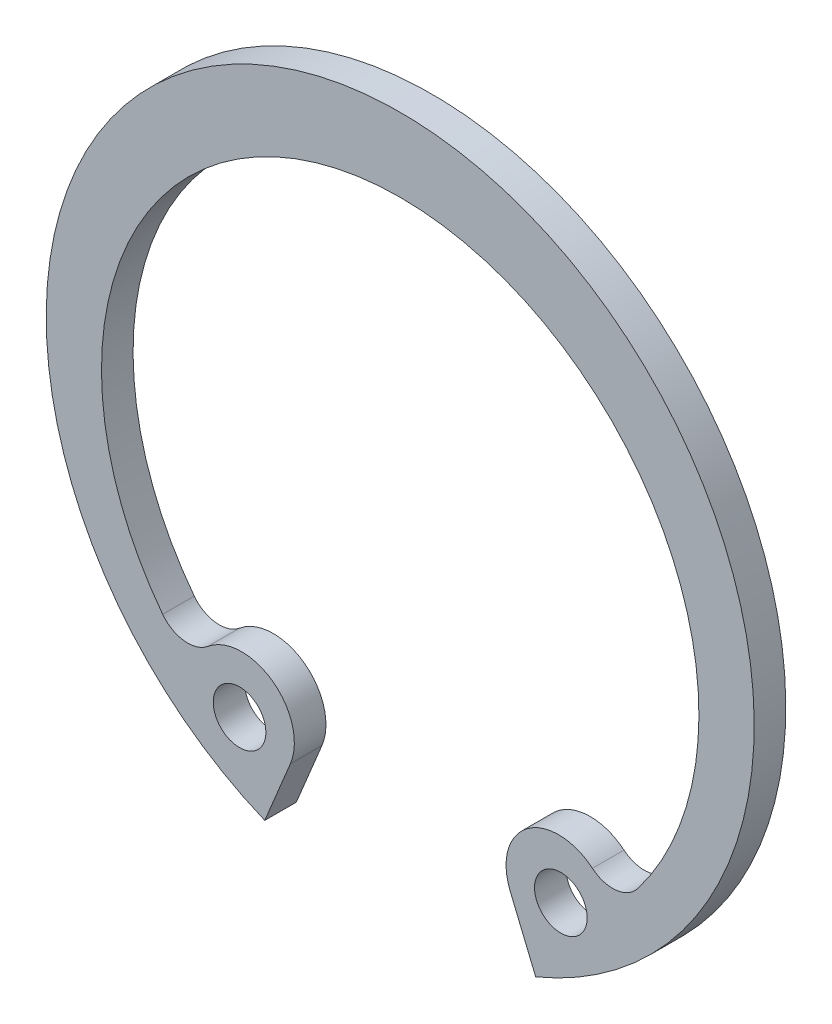
SolidWorks part; units mm, degrees
ref_plane "前视" through (0, 0, 0) normal (0, 0, 1) x (1, 0, 0)
ref_plane "上视" through (0, 0, 0) normal (0, 1, 0) x (1, 0, 0)
ref_plane "右视" through (0, 0, 0) normal (1, 0, 0) x (0, 0, -1)
sketch "尺寸草图" plane through (0, 0, 0) normal (0, 0, 1) x (1, 0, 0)
  line L0 (-13.45, 0) -> (13.45, 0) construction
  line L1 (0, 0) -> (-11.648, -6.725) construction
  circle A0 centre (0, 0) radius 13.45
  point P5 (-9.25, 0)
  point P6 (2, 0)
  point P7 (2, 0)
  point P8 (3.2, 0)
  point P10 (-2.5, 0)
  point P11 (-0.7, 0)
  point P12 (-4.5, 0)
  point P13 (-10.45, 0)
  point P14 (27.3231, 15.775)
  dimension "d3" = 26.9
  dimension "d" = 22.7
  dimension "R1" = 2
  dimension "R2" = 1.2
  dimension "aa" = 45
  dimension "a" = 4.5
  dimension "d5" = 2
  dimension "c" = 0.7
  dimension "s" = 1.2
  dimension "m" = 30
sketch "草图1" plane through (0, 0, 0) normal (0, 0, 1) x (1, 0, 0)
  line L0 (0, 13.45) -> (0, -12.4262) construction
  line L1 (-4.1744, -10.0778) -> (-5.1471, -12.4262)
  line L2 (-6.1855, -9.7068) -> (-6.0221, -9.3125) construction
  line L3 (0, 0) -> (-5.1471, -12.4262) construction
  line L4 (4.1744, -10.0778) -> (5.1471, -12.4262)
  arc A0 (5.1471, -12.4262) -> (-5.1471, -12.4262) centre (0, 0) ccw
  arc A1 (9.0254, -7.5822) -> (-9.0254, -7.5822) centre (0, -0.7) ccw
  circle A2 centre (-6.1038, -9.5097) radius 1
  arc A3 (-4.1744, -10.0778) -> (-7.3028, -7.7763) centre (-6.0221, -9.3125) ccw
  arc A4 (-7.3028, -7.7763) -> (-9.0254, -7.5822) centre (-8.0712, -6.8545) cw
  circle A5 centre (6.1038, -9.5097) radius 1
  arc A6 (4.1744, -10.0778) -> (7.3028, -7.7763) centre (6.0221, -9.3125) cw
  arc A7 (7.3028, -7.7763) -> (9.0254, -7.5822) centre (8.0712, -6.8545) ccw
  dimension "D1" = 26.9
  dimension "D2" = 22.7
  dimension "D5" = 2
  dimension "D7" = 2
  dimension "D8" = 1.2
  dimension "D9" = 4.36
  dimension "D3" = 0.7
  dimension "D4" = 22.5
  dimension "D6" = 11.3
extrude "基体-拉伸" add sketch "草图1" along normal blind 1.2
